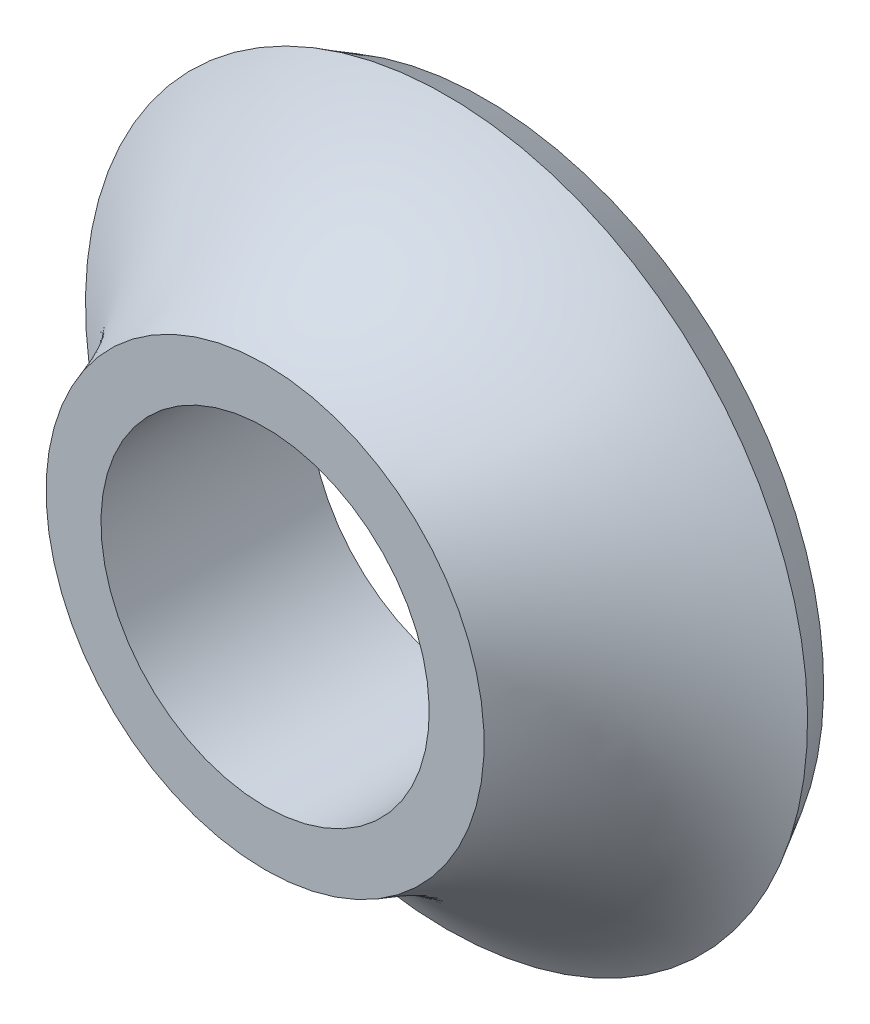
SolidWorks part; units mm, degrees
ref_plane "Front" through (0, 0, 0) normal (0, 0, 1) x (1, 0, 0)
ref_plane "Top" through (0, 0, 0) normal (0, 1, 0) x (1, 0, 0)
ref_plane "Right" through (0, 0, 0) normal (1, 0, 0) x (0, 0, -1)
sketch "Sketch1" plane through (0, 0, 0) normal (1, 0, 0) x (0, 0, -1)
  line L0 (-4.7625, 0) -> (4.7625, 0) construction
  line L1 (-4.7625, 7.1247) -> (-4.7625, 9.5059)
  line L2 (-4.7625, 7.1247) -> (4.2862, 7.1247)
  line L3 (4.2862, 7.1247) -> (4.2862, 9.506)
  line L4 (4.2862, 9.506) -> (2.8575, 9.5059)
  line L5 (2.305, 10.4628) -> (4.7625, 14.7193)
  line L6 (4.7625, 14.7193) -> (3.1127, 15.6718)
  line L7 (4.7625, 0) -> (4.7625, 14.7193) construction
  line L8 (0.4763, 3.5624) -> (0.4763, 1.6574) construction
  line L9 (4.7625, 3.5624) -> (3.81, 3.5624) construction
  line L10 (3.81, 3.5624) -> (2.8575, 3.5624) construction
  line L11 (2.8575, 3.5624) -> (1.905, 3.5624) construction
  line L12 (1.905, 3.5624) -> (0.9525, 3.5624) construction
  line L13 (0.9525, 3.5624) -> (0, 3.5624) construction
  line L14 (0, 3.5624) -> (-0.9525, 3.5624) construction
  line L15 (-0.9525, 3.5624) -> (-1.905, 3.5624) construction
  line L16 (-1.905, 3.5624) -> (-2.8575, 3.5624) construction
  line L17 (4.2863, 3.5624) -> (4.2862, 7.1247) construction
  line L18 (-2.8575, 3.5624) -> (-3.81, 3.5624) construction
  line L19 (-3.81, 3.5624) -> (-4.7625, 3.5624) construction
  line L20 (-4.7625, 0) -> (-4.7625, 3.5624) construction
  line L21 (-4.7625, 7.1247) -> (-4.7625, 3.5624) construction
  line L22 (0.4763, 1.6574) -> (2.8575, 1.6574) construction
  line L23 (-4.7625, -7.1247) -> (4.2862, -7.1247)
  line L24 (2.8575, 3.5624) -> (2.8575, 1.6574) construction
  line L25 (4.7625, -14.7193) -> (3.1127, -15.6718)
  line L26 (2.8575, 1.6574) -> (4.7625, 1.6574) construction
  line L27 (2.305, -10.4628) -> (4.7625, -14.7193)
  line L28 (4.2862, -9.506) -> (2.8575, -9.5059)
  line L29 (4.2862, -7.1247) -> (4.2862, -9.506)
  arc A0 (-4.7625, 9.5059) -> (3.1127, 15.6718) centre (-8.478, 22.3637) ccw
  arc A1 (2.8575, 9.5059) -> (2.305, 10.4628) centre (2.8575, 10.1439) cw
  arc A2 (2.8575, -9.5059) -> (2.305, -10.4628) centre (2.8575, -10.1439) ccw
  dimension "D1" = 30
  dimension "Seal Width" = 9.525
  dimension "Seal ID" = 14.2494
  dimension "Seal OD" = 31.3436
sketch "Sketch4" plane through (0, 0, 0) normal (0, 0, 1) x (1, 0, 0)
  circle A0 centre (0, 0) radius 8.763
  circle A1 centre (0, 0) radius 7.747
  dimension "For Shaft Diameter Max" = 17.526
  dimension "For Shaft Diameter Min" = 15.494
sketch "Sketch3" plane through (0, 0, 0) normal (1, 0, 0) x (0, 0, -1)
  line L0 (-4.7625, 7.1247) -> (-4.7625, 9.5059) construction
  line L1 (4.7625, 14.7193) -> (3.1127, 15.6718) construction
  line L2 (2.305, 10.4628) -> (4.7625, 14.7193) construction
  line L3 (4.2862, 9.506) -> (2.8575, 9.5059) construction
  line L4 (4.2862, 7.1247) -> (4.2862, 9.506) construction
  line L5 (-4.7625, 7.1247) -> (4.2862, 7.1247) construction
  line L6 (-4.7625, 7.1247) -> (-4.7625, 9.5059)
  line L7 (4.7625, 14.7193) -> (3.1127, 15.6718)
  line L8 (2.305, 10.4628) -> (4.7625, 14.7193)
  line L9 (4.2862, 9.506) -> (2.8575, 9.5059)
  line L10 (4.2862, 7.1247) -> (4.2862, 9.506)
  line L11 (-4.7625, 7.1247) -> (4.2862, 7.1247)
  arc A0 (-4.7625, 9.5059) -> (3.1127, 15.6718) centre (-8.478, 22.3637) ccw construction
  arc A1 (2.305, 10.4628) -> (2.8575, 9.5059) centre (2.8575, 10.1439) ccw construction
  arc A2 (-4.7625, 9.5059) -> (3.1127, 15.6718) centre (-8.478, 22.3637) ccw
  arc A3 (2.305, 10.4628) -> (2.8575, 9.5059) centre (2.8575, 10.1439) ccw
revolve "Revolve1" add sketch "Sketch3" angle 360 about L0
sketch "Sketch2" plane through (0, 0, 0) normal (1, 0, 0) x (0, 0, -1)
  line L0 (4.2862, 0) -> (4.2863, 3.5624) construction
  line L1 (-4.7625, 0) -> (4.7625, 0) construction
  line L2 (4.7625, 0) -> (4.2862, 0) construction
  line L3 (4.2862, 0) -> (3.81, 0) construction
  circle A0 centre (4.7625, 0) radius 0.9525
extrude "Cut-Extrude1" cut sketch "Sketch2" against normal up to next and the other way up to next
